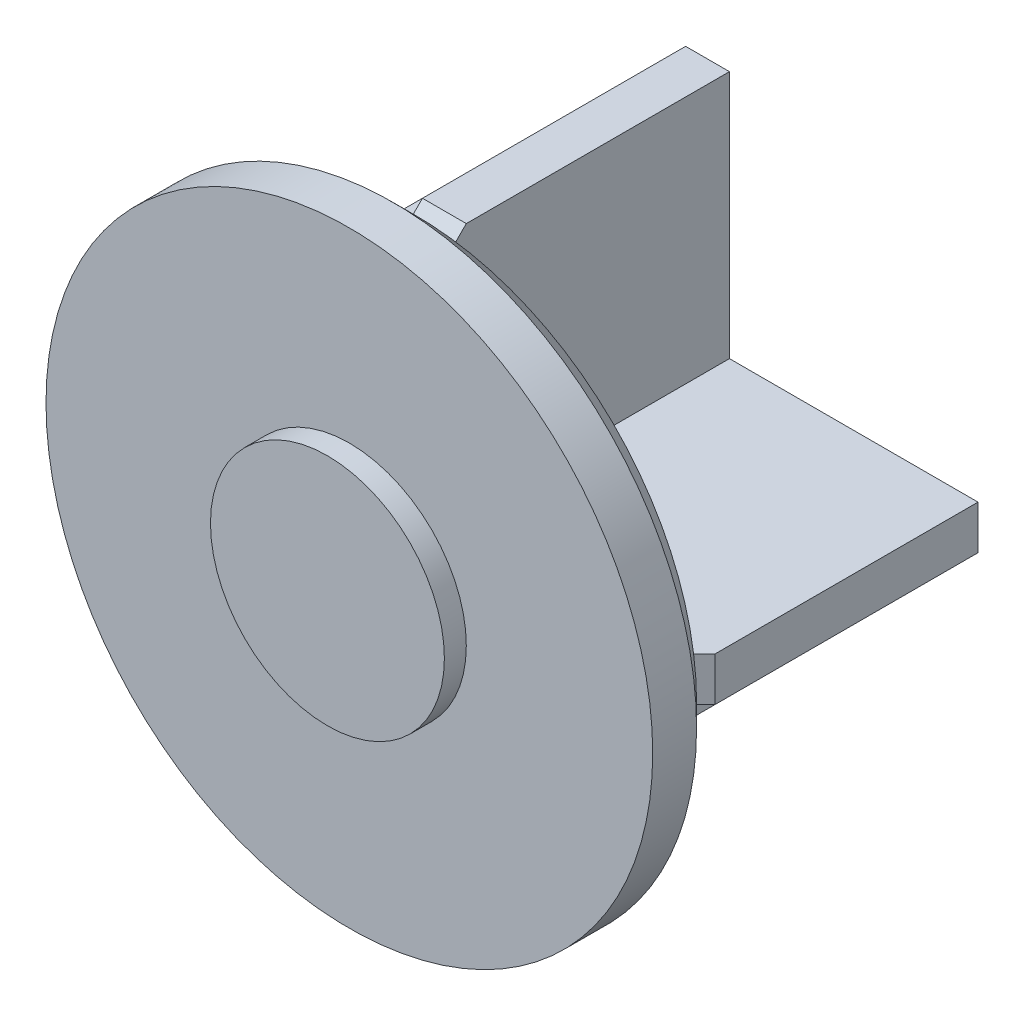
SolidWorks part; units mm, degrees
ref_plane "Front Plane" through (0, 0, 0) normal (0, 0, 1) x (1, 0, 0)
ref_plane "Top Plane" through (0, 0, 0) normal (0, 1, 0) x (1, 0, 0)
ref_plane "Right Plane" through (0, 0, 0) normal (1, 0, 0) x (0, 0, -1)
sketch "Sketch1" plane through (0, 0, 0) normal (0, 0, 1) x (1, 0, 0)
  circle A0 centre (0, 0) radius 41.5
extrude "Boss-Extrude1" add sketch "Sketch1" along normal mid plane 9
chamfer "Chamfer1" distance 3 angle 45 1 edges at (41.5, 0, -4.5)
sketch "Sketch3" plane through (0, 0, 4.5) normal (0, 0, 1) x (1, 0, 0)
  circle A0 centre (0, 0) radius 16
extrude "Boss-Extrude2" add sketch "Sketch3" along normal blind 3
sketch "Sketch4" plane through (0, 0, -4.5) normal (0, 0, -1) x (-1, 0, 0)
  line L1 (3, -37) -> (3, -3)
  line L2 (-37, -3) -> (-3, -3)
  line L3 (-3, -37) -> (-3, -3)
  line L4 (-37, 3) -> (-3, 3)
  line L5 (-3, 37) -> (3, 37)
  line L6 (-3, -37) -> (3, -37)
  line L8 (-37, 3) -> (-37, -3)
  line L9 (37, 3) -> (37, -3)
  line L11 (3, 3) -> (37, 3)
  line L15 (3, -3) -> (37, -3)
  line L17 (3, 3) -> (3, 37)
  line L19 (-3, 3) -> (-3, 37)
  point P0 (0, 0)
  point P11 (0, 0)
extrude "Boss-Extrude3" add sketch "Sketch4" along normal blind 40
sketch "Sketch5" plane through (0, -3, 0) normal (0, -1, 0) x (1, 0, 0)
  line L0 (37, -4.5) -> (37, -8.5)
  line L1 (37, -44.5) -> (37, -4.5) construction
  line L2 (37, -8.5) -> (33, -4.5)
  line L3 (33, -4.5) -> (37, -4.5)
  line L4 (37, -4.5) -> (3, -4.5) construction
  dimension "D1" = 45
extrude "Cut-Extrude1" cut sketch "Sketch5" against normal through all both and the other way through all
pattern_circular "CirPattern1" count 4 over 360 about axis through (0, 0, 0) along (0, 0, 1) of "Cut-Extrude1"
